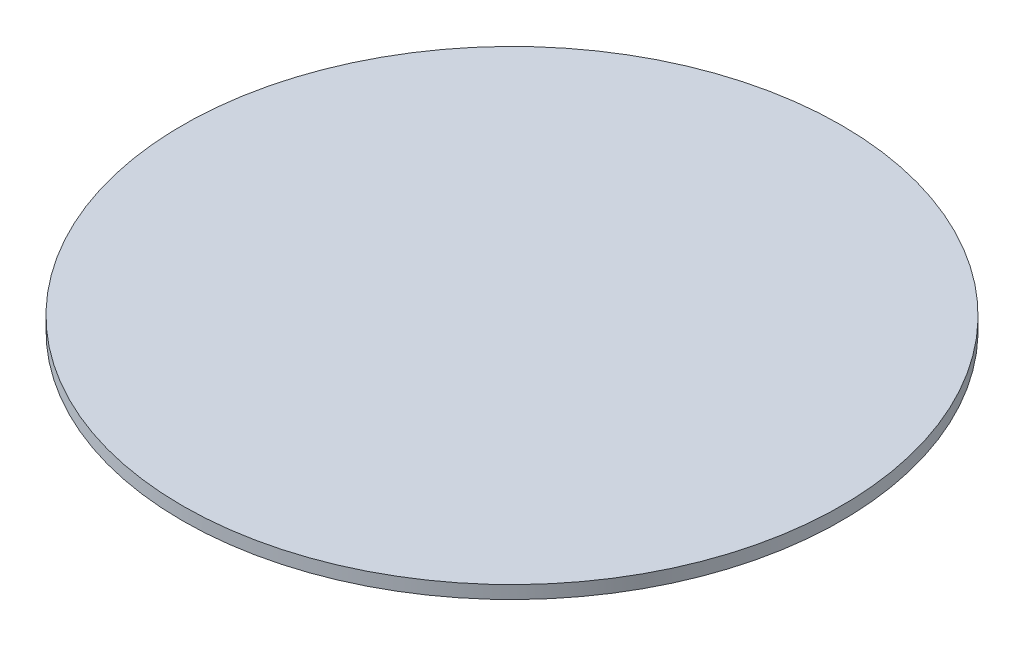
SolidWorks part; units mm, degrees
ref_plane "Front Plane" through (0, 0, 0) normal (0, 0, 1) x (1, 0, 0)
ref_plane "Top Plane" through (0, 0, 0) normal (0, 1, 0) x (1, 0, 0)
ref_plane "Right Plane" through (0, 0, 0) normal (1, 0, 0) x (0, 0, -1)
sketch "Sketch1" plane through (0, 0, 0) normal (0, 1, 0) x (1, 0, 0)
  circle A0 centre (0, 0) radius 12.7
  dimension "D1" = 25.4
extrude "Boss-Extrude1" add sketch "Sketch1" along normal blind 0.5 contours A0
